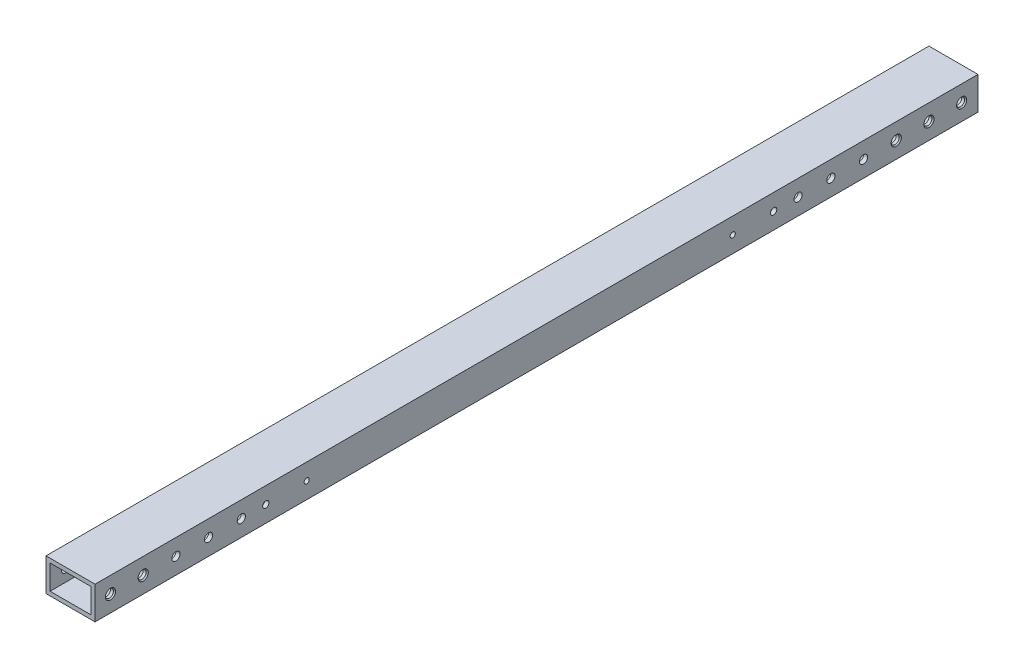
SolidWorks part; units mm, degrees
ref_plane "Front Plane" through (0, 0, 0) normal (0, 0, 1) x (1, 0, 0)
ref_plane "Top Plane" through (0, 0, 0) normal (0, 1, 0) x (1, 0, 0)
ref_plane "Right Plane" through (0, 0, 0) normal (1, 0, 0) x (0, 0, -1)
sketch "Sketch1" plane through (0, 0, 0) normal (0, 0, 1) x (1, 0, 0)
  line L0 (-15.875, 9.525) -> (15.875, 9.525)
  line L2 (-19.05, 12.7) -> (19.05, 12.7)
  line L3 (-19.05, 12.7) -> (-19.05, -12.7)
  line L4 (-19.05, -12.7) -> (19.05, -12.7)
  line L5 (19.05, 12.7) -> (19.05, -12.7)
  line L10 (15.875, 9.525) -> (15.875, -9.525)
  line L11 (-15.875, -9.525) -> (15.875, -9.525)
  line L12 (-15.875, 9.525) -> (-15.875, -9.525)
  point P12 (0, 12.7)
  point P14 (19.05, 0)
  dimension "Wall Thickness" = 3.175
  dimension "Outside Width" = 38.1
  dimension "Outside Height" = 25.4
  dimension "Inside Height" = 19.05
  dimension "Inside Width" = 31.75
sketch "Sketch2" plane through (0, 0, 0) normal (1, 0, 0) x (0, 0, -1)
  line L0 (342.9, 0) -> (-342.9, 0)
  point P4 (0, 0)
  point P7 (-342.9, 0)
  point P10 (342.9, 0)
  dimension "Length" = 685.8
sketch "Sketch3" plane through (0, 0, 0) normal (0, 0, 1) x (1, 0, 0)
  line L21 (19.05, 12.7) -> (-19.05, 12.7)
  line L22 (19.05, -12.7) -> (19.05, 12.7)
  line L23 (-19.05, -12.7) -> (19.05, -12.7)
  line L24 (-19.05, 12.7) -> (-19.05, -12.7)
  line L25 (19.05, 12.7) -> (-19.05, 12.7)
  line L26 (19.05, -12.7) -> (19.05, 12.7)
  line L27 (-19.05, -12.7) -> (19.05, -12.7)
  line L28 (-19.05, 12.7) -> (-19.05, -12.7)
  line L29 (15.875, 9.525) -> (-15.875, 9.525)
  line L30 (15.875, -9.525) -> (15.875, 9.525)
  line L31 (-15.875, -9.525) -> (15.875, -9.525)
  line L32 (-15.875, 9.525) -> (-15.875, -9.525)
  line L33 (15.875, 9.525) -> (-15.875, 9.525)
  line L34 (15.875, -9.525) -> (15.875, 9.525)
  line L35 (-15.875, -9.525) -> (15.875, -9.525)
  line L36 (-15.875, 9.525) -> (-15.875, -9.525)
  dimension "D1" = 0
  dimension "D2" = 0
extrude "Boss-Extrude1" add sketch "Sketch3" along normal up to vertex (342.9 mm away) and the other way up to vertex (342.9 mm away) up to point (0, 0, 342.9) other way up to point (0, 0, -342.9)
sketch "Drawing Reference" plane through (0, 0, 0) normal (1, 0, 0) x (0, 0, -1)
  line L0 (-342.9, 0) -> (342.9, 0) construction
  line L1 (0, -12.7) -> (0, 12.7) construction
  line L2 (-342.9, -12.7) -> (342.9, -12.7) construction
  line L5 (-342.9, 12.7) -> (342.9, 12.7) construction
  point P7 (-315.468, 0)
  point P8 (315.468, 0)
  dimension "D1" = 27.432
sketch "Sketch4" plane through (-19.05, 0, 0) normal (-1, 0, 0) x (0, 0, 1)
  line L0 (-342.9, 0) -> (-330.2, 0)
  line L1 (-342.9, 12.7) -> (-342.9, -12.7) construction
  line L2 (-330.2, 0) -> (-304.8, 0)
  line L3 (-304.8, 0) -> (-279.4, 0)
  line L4 (-279.4, 0) -> (-254, 0)
  line L5 (-254, 0) -> (-228.6, 0)
  line L6 (-228.6, 0) -> (-203.2, 0)
  line L7 (342.9, 0) -> (330.9118, 0)
  line L8 (342.9, 12.7) -> (342.9, -12.7) construction
  line L9 (330.9118, 0) -> (305.5118, 0)
  line L10 (305.5118, 0) -> (280.1118, 0)
  line L11 (280.1118, 0) -> (254.7118, 0)
  line L12 (254.7118, 0) -> (229.3118, 0)
  line L13 (-203.2, 0) -> (-184.15, 0)
  line L14 (-203.2, 0) -> (-152.4, 0) construction
  line L15 (229.3118, 0) -> (210.2618, 0)
  line L16 (229.3118, 0) -> (178.5118, 0) construction
hole_wizard "1/4 (0.25) Diameter Hole2" positions "Sketch7" profile "Sketch8" hole size "1/4" standard "ANSI Inch" end condition through all
sketch "Sketch7" plane through (-19.05, 0, 0) normal (-1, 0, 0) x (0, 0, 1)
  point P0 (-330.2, 0)
  point P3 (-304.8, 0)
  point P7 (330.9118, 0)
  point P11 (-279.4, 0)
  point P14 (305.5118, 0)
sketch "Sketch8" plane through (-19.05, 0, -330.2) normal (0, 1, 0) x (0, 0, 1)
  line L0 (0, 0) -> (0, 38.1)
  line L1 (0, 38.1) -> (3.9624, 38.1)
  line L2 (3.175, 37.1942) -> (3.175, 0)
  line L5 (3.175, 0) -> (0, 0)
  line L7 (3.9624, 38.1) -> (3.175, 37.1942)
  line L8 (-3.9624, 38.1) -> (-3.175, 37.1942) construction
  line L11 (0, -6.35) -> (0, 107.95) construction
  dimension "Thru Hole Dia." = 6.35
  dimension "Thru Hole Depth" = 38.1
  dimension "Far C'Sink Dia." = 7.9248
  dimension "Far C'Sink Angle" = 82
hole_wizard "1/4 (0.25) Diameter Hole3" positions "Sketch9" profile "Sketch10" hole size "1/4" standard "ANSI Inch" end condition through all
sketch "Sketch9" plane through (19.05, 0, 0) normal (1, 0, 0) x (0, 0, -1)
  point P0 (-280.1118, 0)
  point P3 (-254.7118, 0)
  point P6 (-229.3118, 0)
  point P9 (254, 0)
  point P12 (228.6, 0)
  point P15 (203.2, 0)
sketch "Sketch10" plane through (19.05, 0, 280.1118) normal (0, 1, 0) x (0, 0, -1)
  line L0 (0, 0) -> (0, 38.1)
  line L1 (0, 38.1) -> (3.175, 38.1)
  line L2 (3.175, 38.1) -> (3.175, 0)
  line L5 (3.175, 0) -> (0, 0)
  line L11 (0, -6.35) -> (0, 107.95) construction
  dimension "Thru Hole Dia." = 6.35
  dimension "Thru Hole Depth" = 38.1
hole_wizard "5/32 (0.15625) Diameter Hole1" positions "Sketch11" profile "Sketch12" hole size "5/32" standard "ANSI Inch" end condition through all
sketch "Sketch11" plane through (19.05, 0, 0) normal (1, 0, 0) x (0, 0, -1)
  point P0 (152.4, 0)
  point P3 (-178.5118, 0)
sketch "Sketch12" plane through (19.05, 0, -152.4) normal (0, 1, 0) x (0, 0, -1)
  line L0 (0, 0) -> (0, 38.1)
  line L1 (0, 38.1) -> (1.9844, 38.1)
  line L2 (1.9844, 38.1) -> (1.9844, 0)
  line L5 (1.9844, 0) -> (0, 0)
  line L11 (0, -6.35) -> (0, 107.95) construction
  dimension "Thru Hole Dia." = 3.9688
  dimension "Thru Hole Depth" = 38.1
hole_wizard "#10 (0.1935) Diameter Hole1" positions "Sketch13" profile "Sketch14" hole size "#10" standard "ANSI Inch" end condition through all
sketch "Sketch13" plane through (-19.05, 0, 0) normal (-1, 0, 0) x (0, 0, 1)
  point P0 (-184.15, 0)
  point P3 (210.2618, 0)
sketch "Sketch14" plane through (-19.05, 0, -184.15) normal (0, 1, 0) x (0, 0, 1)
  line L0 (0, 0) -> (0, 38.1)
  line L1 (0, 38.1) -> (2.4574, 38.1)
  line L2 (2.4574, 38.1) -> (2.4574, 0)
  line L5 (2.4574, 0) -> (0, 0)
  line L11 (0, -6.35) -> (0, 107.95) construction
  dimension "Thru Hole Dia." = 4.9149
  dimension "Thru Hole Depth" = 38.1
equation "\"D1@Drawing Reference\"=\"Outside Width@Sketch1\" * 0.72"
